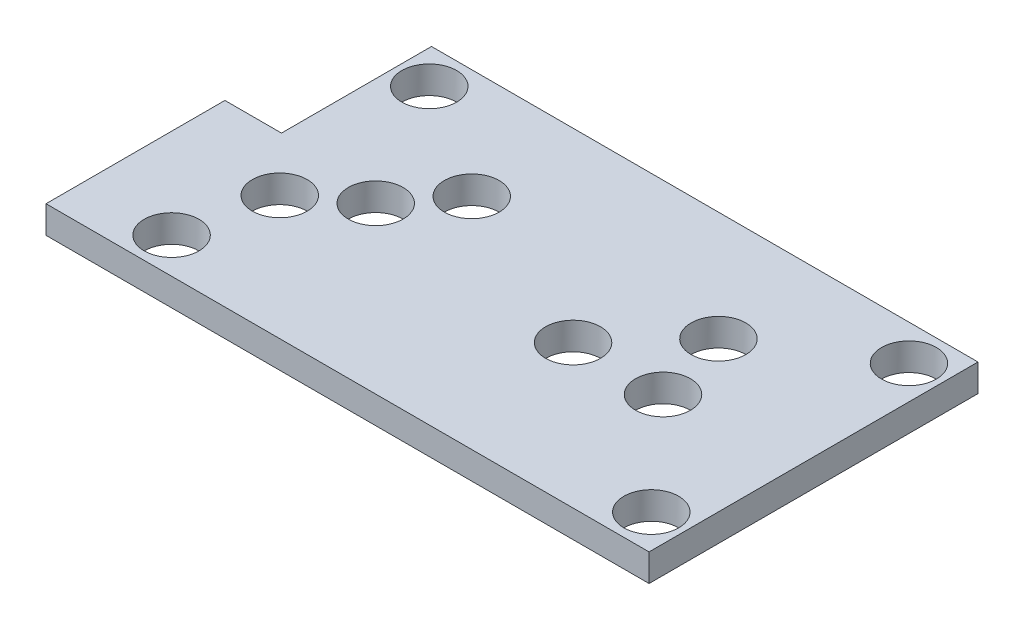
SolidWorks part; units mm, degrees
material "K110"
ref_plane "Front Plane" through (0, 0, 0) normal (0, 0, 1) x (1, 0, 0)
ref_plane "Top Plane" through (0, 0, 0) normal (0, 1, 0) x (1, 0, 0)
ref_plane "Right Plane" through (0, 0, 0) normal (1, 0, 0) x (0, 0, -1)
sketch "Sketch1" plane through (0, 0, 0) normal (0, 1, 0) x (1, 0, 0)
  line L1 (-110, -60) -> (110, -60)
  line L2 (-110, -60) -> (-110, 60)
  line L3 (-110, 60) -> (110, 60)
  line L4 (110, -60) -> (110, 60)
  line L5 (-110, -60) -> (110, 60) construction
  line L6 (-110, 60) -> (110, -60) construction
  point P0 (0, 0)
  dimension "D1" = 120
  dimension "D2" = 220
extrude "Boss-Extrude1" add sketch "Sketch1" against normal blind 10
sketch "Sketch2" plane through (0, 0, 0) normal (0, 1, 0) x (1, 0, 0)
  line L1 (-110, 60) -> (-89.3675, 60)
  line L2 (-110, 60) -> (-110, 5.27)
  line L3 (-110, 5.27) -> (-89.3675, 5.27)
  line L4 (-89.3675, 60) -> (-89.3675, 5.27)
  line L5 (-90, -14.72) -> (-89.3675, 5.27) construction
  line L10 (-70, 0.28) -> (-89.3675, 5.27) construction
  circle A0 centre (-70, 0.28) radius 3.1 construction
  circle A1 centre (-90, -14.72) radius 3.1 construction
  dimension "D1" = 20
extrude "Cut-Extrude1" cut sketch "Sketch2" against normal up to next
sketch "Sketch3" plane through (0, 0, 0) normal (0, 1, 0) x (1, 0, 0)
  circle A0 centre (97.8163, -47) radius 10 construction
  circle A1 centre (-77.1837, -47) radius 10 construction
  circle A2 centre (-70, -14.72) radius 10 construction
  circle A3 centre (-50, 0.28) radius 10 construction
  circle A4 centre (30, -7.72) radius 10 construction
  circle A5 centre (62.8163, -7.72) radius 10 construction
  circle A6 centre (55.3163, 20) radius 10 construction
  circle A7 centre (97.8163, 47) radius 10 construction
  circle A8 centre (-34.6837, 20) radius 10 construction
  circle A9 centre (-77.1837, 47) radius 10 construction
  circle A10 centre (97.8163, -47) radius 10
  circle A11 centre (-77.1837, -47) radius 10
  circle A12 centre (-70, -14.72) radius 10
  circle A13 centre (-50, 0.28) radius 10
  circle A14 centre (30, -7.72) radius 10
  circle A15 centre (62.8163, -7.72) radius 10
  circle A16 centre (55.3163, 20) radius 10
  circle A17 centre (97.8163, 47) radius 10
  circle A18 centre (-34.6837, 20) radius 10
  circle A19 centre (-77.1837, 47) radius 10
extrude "Cut-Extrude2" cut sketch "Sketch3" against normal up to next
